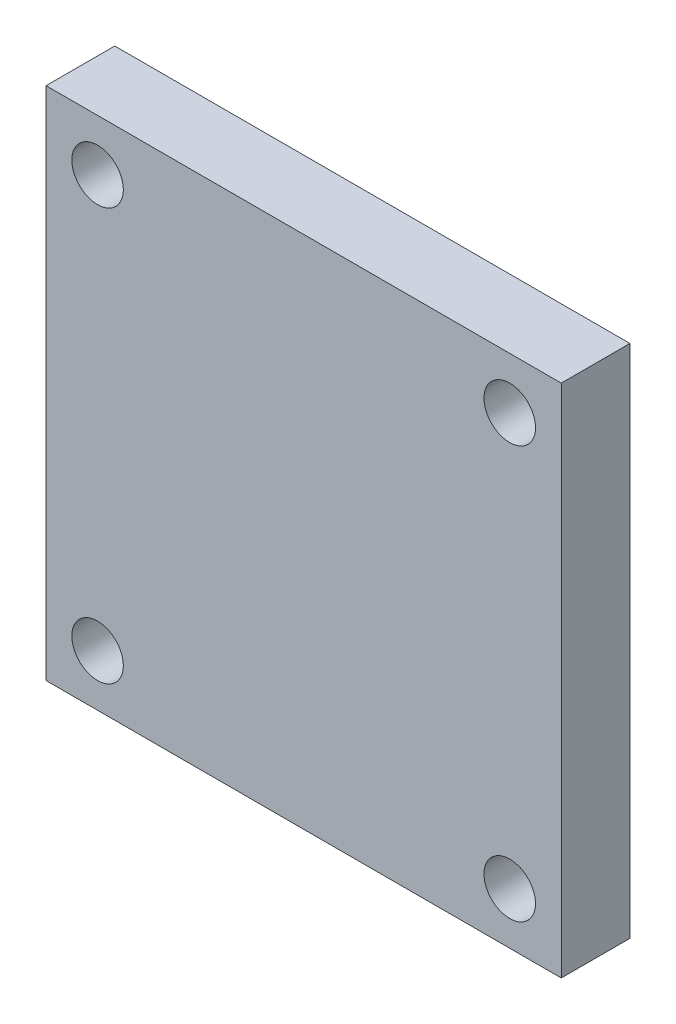
SolidWorks part; units mm, degrees
ref_plane "Front Plane" through (0, 0, 0) normal (0, 0, 1) x (1, 0, 0)
ref_plane "Top Plane" through (0, 0, 0) normal (0, 1, 0) x (1, 0, 0)
ref_plane "Right Plane" through (0, 0, 0) normal (1, 0, 0) x (0, 0, -1)
sketch "Esquisse1" plane through (0, 0, 0) normal (0, 0, 1) x (1, 0, 0)
  line L1 (0, 0) -> (30, 0)
  line L2 (0, 0) -> (0, -30)
  line L3 (0, -30) -> (30, -30)
  line L4 (30, 0) -> (30, -30)
  line L5 (0, 0) -> (30, -30) construction
  line L6 (0, -30) -> (30, 0) construction
  circle A0 centre (3, -3) radius 1.5
  circle A1 centre (3, -27) radius 1.5
  circle A2 centre (27, -3) radius 1.5
  circle A3 centre (27, -27) radius 1.5
  point P0 (15, -15)
  point P13 (-49.8047, 21.5389)
  point P14 (0, 0)
  dimension "D3" = 3
  dimension "D4" = 3
  dimension "D5" = 3
  dimension "D6" = 3
  dimension "D1" = 30
  dimension "D2" = 30
  dimension "D7" = 3
  dimension "D8" = 3
  dimension "D9" = 3
  dimension "D10" = 3
extrude "Boss.-Extru.1" add sketch "Esquisse1" along normal blind 4
